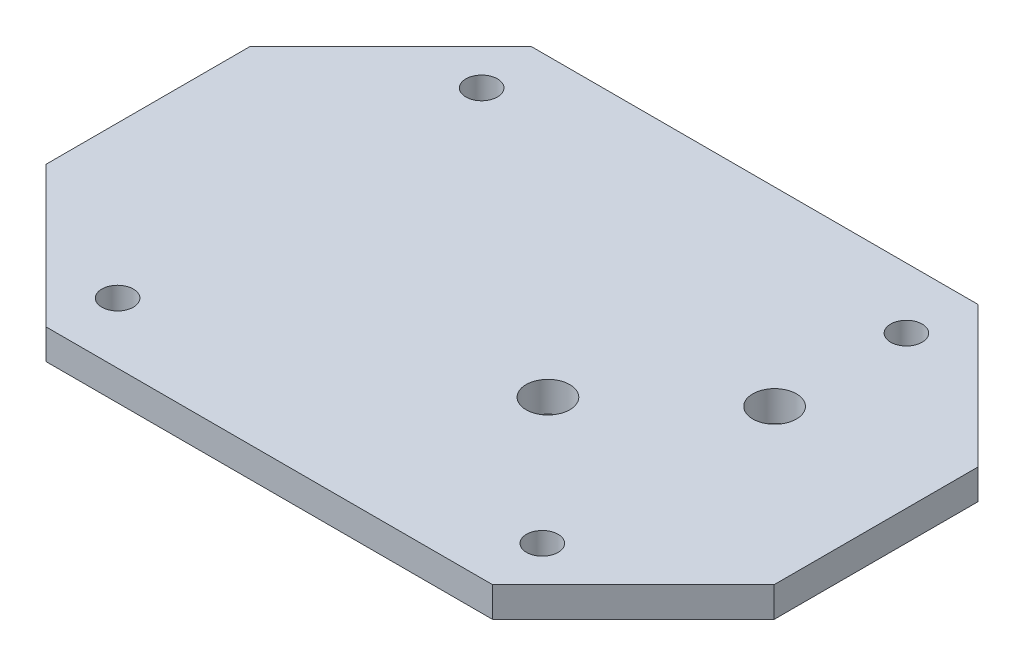
SolidWorks part; units mm, degrees
material "Acrylic (Medium-high impact)"
ref_plane "Front Plane" through (0, 0, 0) normal (0, 0, 1) x (1, 0, 0)
ref_plane "Top Plane" through (0, 0, 0) normal (0, 1, 0) x (1, 0, 0)
ref_plane "Right Plane" through (0, 0, 0) normal (1, 0, 0) x (0, 0, -1)
sketch "Sketch1" plane through (0, 0, 0) normal (0, 1, 0) x (1, 0, 0)
  line L0 (23.368, -25.4) -> (38.1, -10.668)
  line L1 (-23.368, 25.4) -> (23.368, 25.4)
  line L2 (-38.1, 10.668) -> (-38.1, -10.668)
  line L3 (-23.368, -25.4) -> (23.368, -25.4)
  line L4 (38.1, 10.668) -> (38.1, -10.668)
  line L5 (-52.832, 25.4) -> (23.368, -25.4) construction
  line L6 (-52.832, -25.4) -> (23.368, 25.4) construction
  line L7 (-2.54, -10.668) -> (41.529, -10.668) construction
  line L8 (0, -25.4) -> (0, 25.4) construction
  line L9 (-38.1, 0) -> (38.1, 0) construction
  line L10 (-23.368, -25.4) -> (-38.1, -10.668)
  line L11 (23.368, 25.4) -> (38.1, 10.668)
  line L12 (-23.368, 25.4) -> (-38.1, 10.668)
  circle A0 centre (-22.225, 19.05) radius 1.651
  circle A1 centre (22.225, 19.05) radius 1.651
  circle A2 centre (22.225, -19.05) radius 1.651
  circle A3 centre (-22.225, -19.05) radius 1.651
  circle A5 centre (9.271, -5.5118) radius 2.286
  circle A6 centre (21.971, 5.5118) radius 2.286
  point P0 (-14.732, 0)
  dimension "D1" = 50.8
  dimension "D2" = 76.2
  dimension "D3" = 45
  dimension "D4" = 14.732
extrude "Boss-Extrude1" add sketch "Sketch1" along normal blind 3.1496
